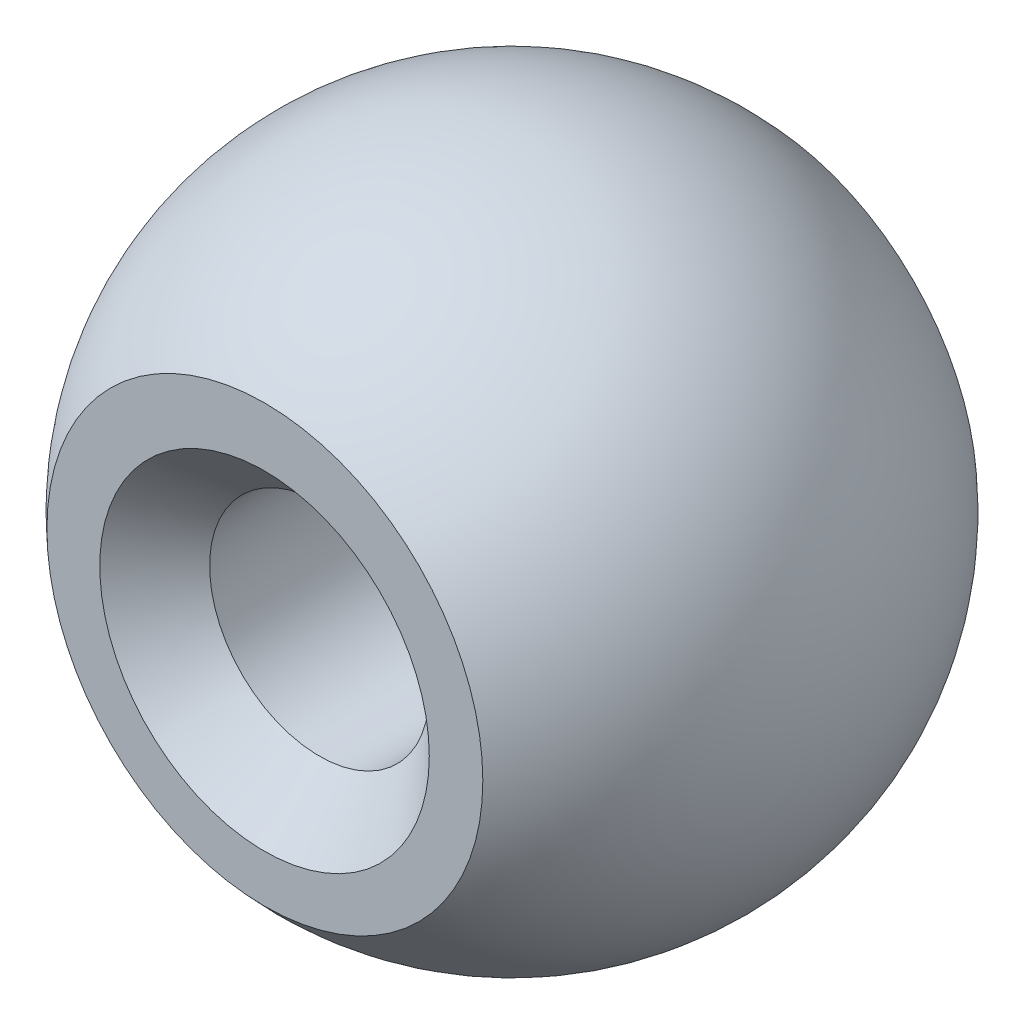
SolidWorks part; units mm, degrees
ref_plane "Front Plane" through (0, 0, 0) normal (0, 0, 1) x (1, 0, 0)
ref_plane "Top Plane" through (0, 0, 0) normal (0, 1, 0) x (1, 0, 0)
ref_plane "Right Plane" through (0, 0, 0) normal (1, 0, 0) x (0, 0, -1)
sketch "Sketch1" plane through (0, 0, 0) normal (0, 1, 0) x (1, 0, 0)
  line L0 (0, 6.5666) -> (0, 6) construction
  line L1 (0, 4.5) -> (3.9686, 4.5)
  line L2 (0, -4.5) -> (3.9686, -4.5)
  line L6 (0, 0) -> (5.3508, 2.7145) construction
  line L7 (0, 0) -> (7.616, -3.8637) construction
  line L8 (0, 4.5) -> (0, -8.6654) construction
  line L9 (0, 4.5) -> (0, -4.5)
  arc A0 (3.9686, -4.5) -> (3.9686, 4.5) centre (0, 0) ccw
  point P7 (1.9843, 4.5)
  point P12 (0, 0)
  point P13 (0, 0)
  point P14 (0, 0)
  point P15 (0, 0)
  point P16 (0, 0)
  dimension "D1" = 6
  dimension "D2" = 9
revolve "Revolve1" add sketch "Sketch1" angle 360 about L8
hole_wizard "CSK for M2 Flat Head Machine Screw3" positions "3DSketch3" profile "Sketch4" countersink size "M2" standard "ANSI Metric" end condition through all
sketch3d "3DSketch3"
  point P0 (-0.006, -0.1033, 4.5)
  point P2 (-0.006, -0.1033, 4.5)
  point P4 (-0.006, -0.1033, 4.5)
  point P5 (0, 0, 0)
sketch "Sketch4" plane through (-0.006, -0.1033, 4.5) normal (1, 0, 0) x (0, -1, 0)
  line L0 (0, 0) -> (0, 9)
  line L1 (0, 9) -> (2, 9)
  line L2 (2, 9) -> (2, 1)
  line L3 (2, 1) -> (3, 0)
  line L5 (3, 0) -> (0, 0)
  line L6 (-2, 1) -> (-3, 0) construction
  line L11 (0, -6.35) -> (0, 107.95) construction
  dimension "Thru Hole Dia." = 4
  dimension "Thru Hole Depth" = 9
  dimension "Near C'Sink Dia." = 6
  dimension "Near C'Sink Angle" = 90
